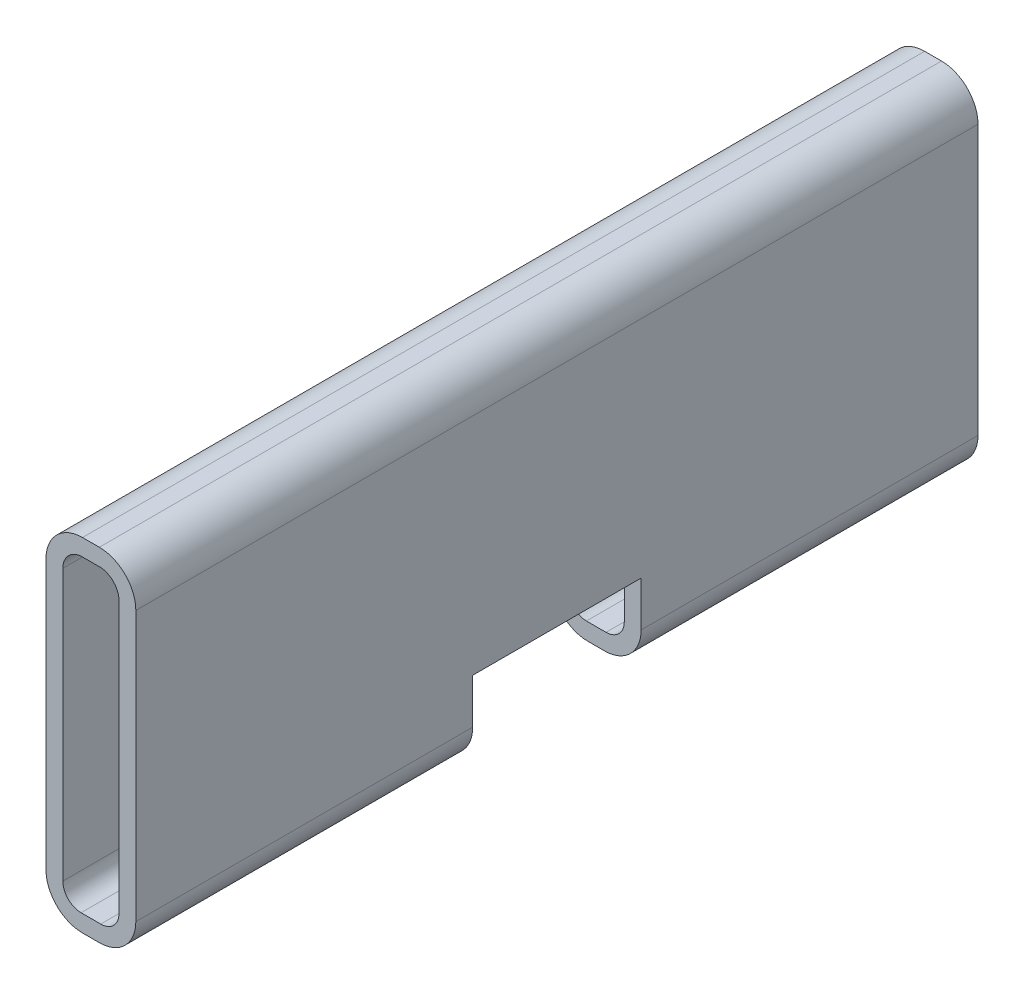
SolidWorks part; units mm, degrees
ref_plane "Piano frontale" through (0, 0, 0) normal (0, 0, 1) x (1, 0, 0)
ref_plane "Piano superiore" through (0, 0, 0) normal (0, 1, 0) x (1, 0, 0)
ref_plane "Piano destro" through (0, 0, 0) normal (1, 0, 0) x (0, 0, -1)
sketch "Schizzo1" plane through (0, 0, 0) normal (0, 0, 1) x (1, 0, 0)
  line L1 (0, 0) -> (-16, 0)
  line L2 (0, 0) -> (0, 61)
  line L3 (0, 61) -> (-16, 61)
  line L4 (-16, 0) -> (-16, 61)
  line L5 (-3, 3) -> (-13, 3)
  line L6 (-3, 3) -> (-3, 58)
  line L7 (-3, 58) -> (-13, 58)
  line L8 (-13, 3) -> (-13, 58)
  dimension "D1" = 3
  dimension "D2" = 3
  dimension "D3" = 3
  dimension "D4" = 3
  dimension "D5" = 55
  dimension "D6" = 10
extrude "Estrusione-Estrusione2" add sketch "Schizzo1" along normal blind 60
fillet "Raccordo1" radius 6.5 4 edges at (-16, 61, 30) (-16, 0, 30) (0, 0, 30) (0, 61, 30)
fillet "Raccordo2" radius 3.25 4 edges at (-3, 3, 30) (-13, 3, 30) (-3, 58, 30) (-13, 58, 30)
sketch "Schizzo2" plane through (0, 0, 60) normal (0, 0, 1) x (1, 0, 0)
  line L0 (-16, 14.5) -> (-16, 54.5)
  line L1 (-16, 54.5) -> (-16, 6.5) construction
  line L3 (-9.5, 61) -> (-6.5, 61)
  line L5 (-13, 14.5) -> (-13, 54.5)
  line L6 (-13, 54.75) -> (-13, 6.25) construction
  line L7 (-3, 14.5) -> (-3, 54.5)
  line L8 (-3, 6.25) -> (-3, 54.75) construction
  line L10 (-16, 14.5) -> (-13, 14.5)
  line L12 (-9.75, 58) -> (-6.25, 58)
  line L14 (0, 54.5) -> (0, 14.5)
  line L15 (0, 6.5) -> (0, 54.5) construction
  line L16 (0, 14.5) -> (-3, 14.5)
  arc A5 (-16, 54.5) -> (-9.5, 61) centre (-9.5, 54.5) cw
  arc A7 (-13, 54.5) -> (-9.75, 58) centre (-9.4904, 54.5) cw
  arc A8 (-3, 54.5) -> (-6.25, 58) centre (-6.5096, 54.5) ccw
  arc A9 (0, 54.5) -> (-6.5, 61) centre (-6.5, 54.5) ccw
  dimension "D1" = 40
extrude "Estrusione-Estrusione3" add sketch "Schizzo2" along normal blind 30
sketch "Schizzo3" plane through (0, 0, 90) normal (0, 0, 1) x (1, 0, 0)
  line L0 (-16, 6.5) -> (-16, 54.5)
  line L2 (0, 54.5) -> (0, 6.5)
  line L3 (-13, 54.5) -> (-13, 6.25)
  line L4 (-3, 6.25) -> (-3, 54.5)
  line L6 (-9.75, 3) -> (-6.25, 3)
  line L7 (-9.5, 0) -> (-6.5, 0)
  line L8 (-16, 54.5) -> (-16, 14.5) construction
  line L9 (-13, 14.5) -> (-13, 54.5) construction
  line L10 (0, 14.5) -> (0, 54.5) construction
  line L11 (-9.75, 58) -> (-6.25, 58)
  line L12 (-9.5, 61) -> (-6.5, 61)
  arc A4 (-16, 6.5) -> (-9.5, 0) centre (-9.5, 6.5) ccw
  arc A5 (0, 6.5) -> (-6.5, 0) centre (-6.5, 6.5) cw
  arc A6 (-3, 6.25) -> (-6.25, 3) centre (-6.25, 6.25) cw
  arc A7 (-13, 6.25) -> (-9.75, 3) centre (-9.75, 6.25) ccw
  arc A10 (-16, 54.5) -> (-9.5, 61) centre (-9.5, 54.5) cw
  arc A11 (0, 54.5) -> (-6.5, 61) centre (-6.5, 54.5) ccw
  arc A12 (-13, 54.5) -> (-9.75, 58) centre (-9.4904, 54.5) cw
  arc A13 (-3, 54.5) -> (-6.25, 58) centre (-6.5096, 54.5) ccw
extrude "Estrusione-Estrusione4" add sketch "Schizzo3" along normal blind 60
